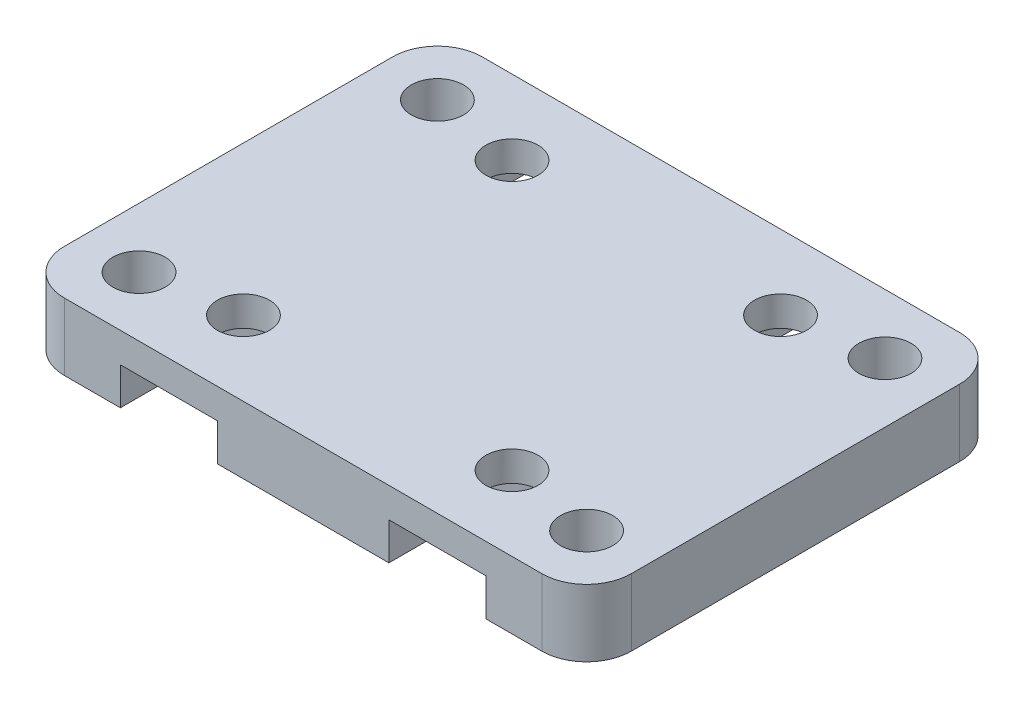
SolidWorks part; units mm, degrees
ref_plane "前基準面" through (0, 0, 0) normal (0, 0, 1) x (1, 0, 0)
ref_plane "上基準面" through (0, 0, 0) normal (0, 1, 0) x (1, 0, 0)
ref_plane "右基準面" through (0, 0, 0) normal (1, 0, 0) x (0, 0, -1)
sketch "草圖1" plane through (0, 0, 0) normal (0, 1, 0) x (1, 0, 0)
  line L1 (-19, -14) -> (19, -14)
  line L2 (-19, -14) -> (-19, 14)
  line L3 (-19, 14) -> (19, 14)
  line L4 (19, -14) -> (19, 14)
  line L5 (-19, -14) -> (19, 14) construction
  line L6 (-19, 14) -> (19, -14) construction
  point P0 (0, 0)
  dimension "D1" = 28
  dimension "D2" = 38
extrude "填料-伸長1" add sketch "草圖1" along normal mid plane 4.5
hole_wizard "Ø3.5 (3.5) 直徑孔2" positions "草圖3" profile "草圖4" hole size "Ø3.5" standard "ISO" end condition through all
sketch "草圖3" plane through (0, 2.25, 0) normal (0, 1, 0) x (1, 0, 0)
  line L1 (-15, -10) -> (15, -10)
  line L2 (-15, -10) -> (-15, 10)
  line L3 (-15, 10) -> (15, 10)
  line L4 (15, -10) -> (15, 10)
  line L5 (-15, -10) -> (15, 10) construction
  line L6 (-15, 10) -> (15, -10) construction
  point P2 (15, 10)
  point P51 (-15, -10)
  point P52 (-15, 10)
  point P53 (15, -10)
  dimension "D1" = 30
  dimension "D2" = 20
sketch "草圖4" plane through (15, 2.25, -10) normal (1, 0, 0) x (0, 0, 1)
  line L0 (0, 0) -> (0, 4.5)
  line L1 (0, 4.5) -> (1.75, 4.5)
  line L2 (1.75, 4.5) -> (1.75, 0)
  line L5 (1.75, 0) -> (0, 0)
  line L11 (0, -6.35) -> (0, 107.95) construction
  dimension "砮 ふ 畖" = 3.5
  dimension "砮 ふ瞏 " = 4.5
hole_wizard "Ø3.5 (3.5) 直徑孔4" positions "草圖7" profile "草圖8" hole size "Ø3.5" standard "ISO" end condition through all
sketch "草圖7" plane through (0, 2.25, 0) normal (0, 1, 0) x (1, 0, 0)
  line L1 (-9, -9) -> (9, -9)
  line L2 (-9, -9) -> (-9, 9)
  line L3 (-9, 9) -> (9, 9)
  line L4 (9, -9) -> (9, 9)
  line L5 (-9, -9) -> (9, 9) construction
  line L6 (-9, 9) -> (9, -9) construction
  point P2 (9, 9)
  point P99 (-9, -9)
  point P100 (-9, 9)
  point P101 (9, -9)
  dimension "D1" = 18
sketch "草圖8" plane through (9, 2.25, -9) normal (1, 0, 0) x (0, 0, 1)
  line L0 (0, 0) -> (0, 4.5)
  line L1 (0, 4.5) -> (1.75, 4.5)
  line L2 (1.75, 4.5) -> (1.75, 0)
  line L5 (1.75, 0) -> (0, 0)
  line L11 (0, -6.35) -> (0, 107.95) construction
  dimension "砮 ふ 畖" = 3.5
  dimension "砮 ふ瞏 " = 4.5
sketch "草圖9" plane through (0, -2.25, 0) normal (0, -1, 0) x (1, 0, 0)
  line L0 (-12.25, 10.8764) -> (-12.25, 14)
  line L1 (-9, 12.7528) -> (-12.25, 10.8764) construction
  line L2 (-12.25, 10.8764) -> (-12.25, 7.1236)
  line L3 (-12.25, 7.1236) -> (-9, 5.2472)
  line L4 (-9, 5.2472) -> (-5.75, 7.1236)
  line L5 (-5.75, 7.1236) -> (-5.75, 10.8764)
  line L6 (-5.75, 10.8764) -> (-9, 12.7528) construction
  line L7 (-12.25, 14) -> (-5.75, 14)
  line L8 (-5.75, 14) -> (-5.75, 10.8764)
  line L9 (-19, 14) -> (19, 14) construction
  circle A0 centre (-9, 9) radius 3.25 construction
  dimension "D1" = 6.5
extrude "除料-伸長2" cut sketch "草圖9" against normal blind 2.5
mirror "鏡射3" about plane through (0, 0, 0) normal (0, 0, 1) of "除料-伸長2"
mirror "鏡射4" about plane through (0, 0, 0) normal (1, 0, 0) of "鏡射3", "除料-伸長2"
fillet "圓角2" radius 3 4 edges at (-19, 0, -14) (19, 0, -14) (19, 0, 14) (-19, 0, 14)
